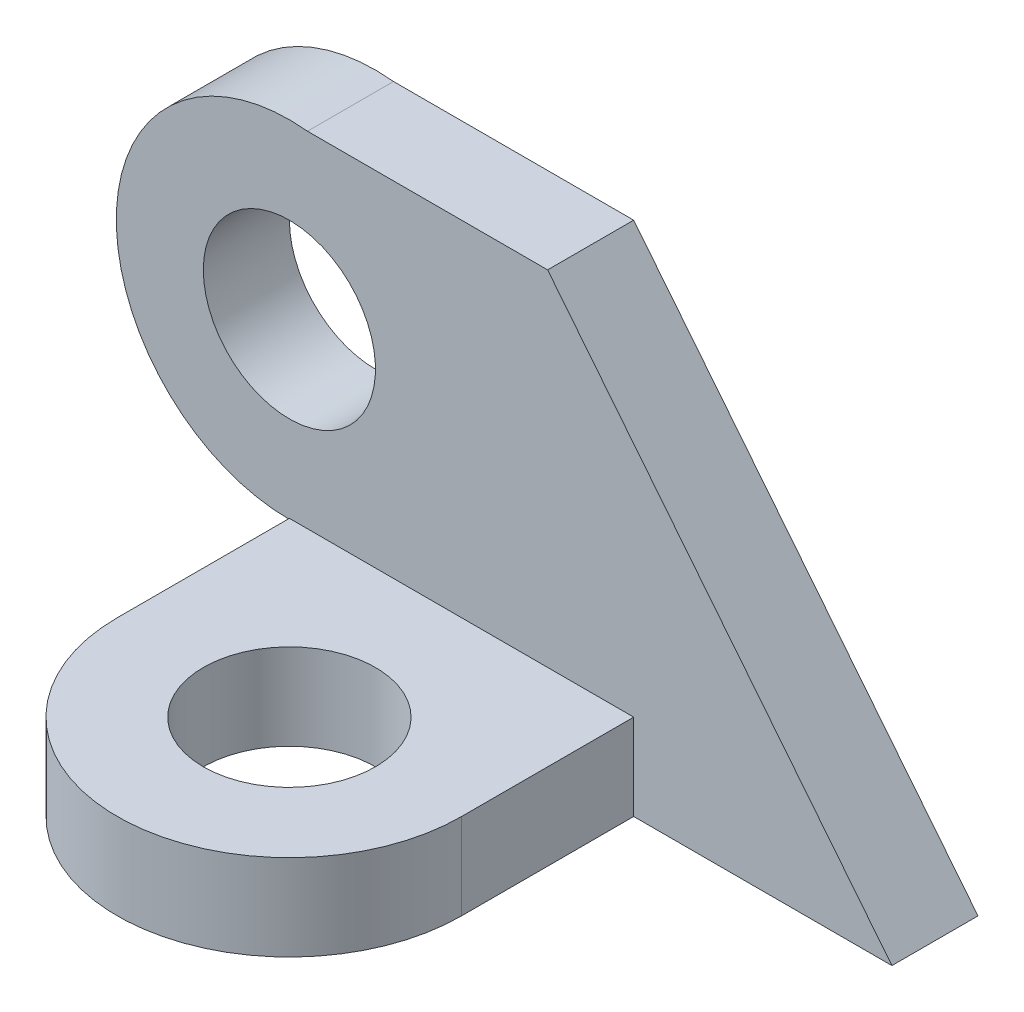
SolidWorks part; units mm, degrees
ref_plane "Front Plane" through (0, 0, 0) normal (0, 0, 1) x (1, 0, 0)
ref_plane "Top Plane" through (0, 0, 0) normal (0, 1, 0) x (1, 0, 0)
ref_plane "Right Plane" through (0, 0, 0) normal (1, 0, 0) x (0, 0, -1)
sketch "Sketch1" plane through (0, 0, 0) normal (0, 1, 0) x (1, 0, 0)
  line L0 (-20, 0) -> (-20, 20)
  line L1 (-20, 20) -> (20, 20)
  line L2 (20, 20) -> (20, 0)
  circle A0 centre (0, 0) radius 10
  arc A1 (-20, 0) -> (20, 0) centre (0, 0) ccw
  dimension "D1" = 20
  dimension "D2" = 40
extrude "Boss-Extrude1" add sketch "Sketch1" along normal blind 10
sketch "Sketch2" plane through (0, 0, -20) normal (0, 0, -1) x (-1, 0, 0)
  line L0 (20, 10) -> (20, 50) construction
  line L1 (20, 50) -> (-10, 50)
  line L2 (20, 10) -> (20, 0)
  line L3 (20, 10) -> (20, 0) construction
  line L4 (20, 0) -> (-50, 0)
  line L5 (-10, 50) -> (-50, 0)
  arc A0 (20, 9.8902) -> (17.9011, 50) centre (20, 30) ccw
  circle A1 centre (20, 30) radius 10
  line M8 (20, 10) -> (-20, 10)
  line M9 (-20, 10) -> (-20, 0)
  dimension "D2" = 20
  dimension "D1" = 40
  dimension "D3" = 70
  dimension "D4" = 30
extrude "Boss-Extrude2" add sketch "Sketch2" along normal blind 10 separate body contours L0 L2 A0 L1 A1 | L0 A1 L1 L5 L4 M8 M9
